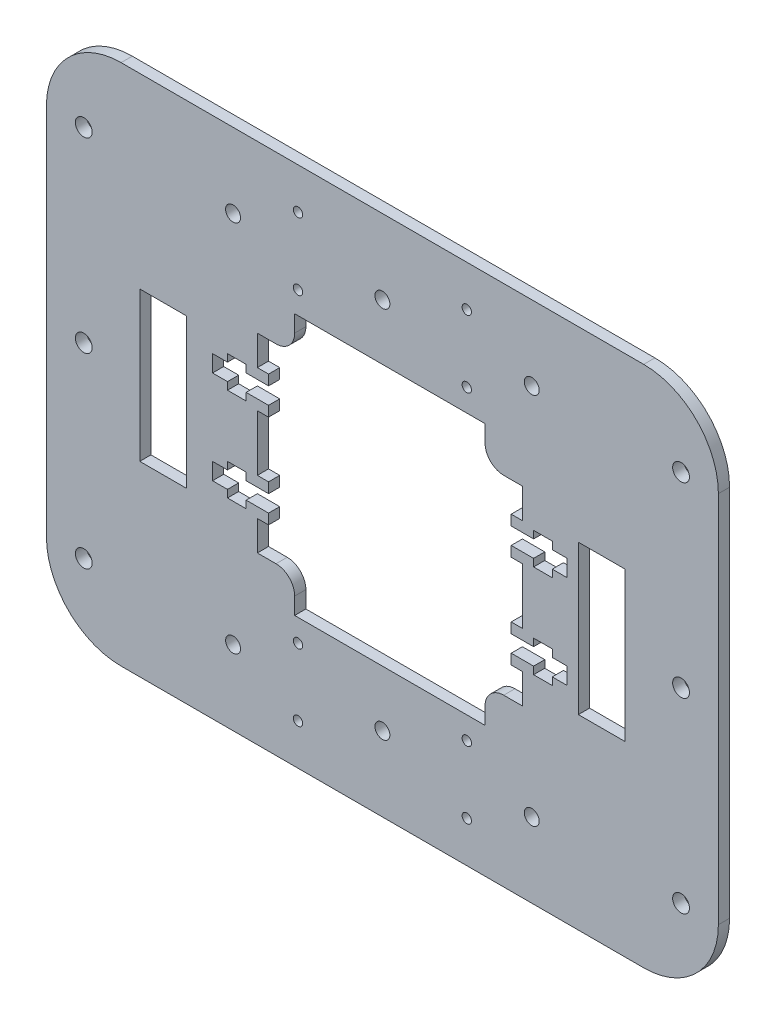
SolidWorks part; units mm, degrees
ref_plane "前视基准面" through (0, 0, 0) normal (0, 0, 1) x (1, 0, 0)
ref_plane "上视基准面" through (0, 0, 0) normal (0, 1, 0) x (1, 0, 0)
ref_plane "右视基准面" through (0, 0, 0) normal (1, 0, 0) x (0, 0, -1)
sketch "草图1" plane through (0, 0, 0) normal (0, 0, 1) x (1, 0, 0)
  line L1 (-90, 70) -> (90, 70)
  line L2 (-90, 70) -> (-90, -70)
  line L3 (-90, -70) -> (90, -70)
  line L4 (90, 70) -> (90, -70)
  line L5 (-90, 70) -> (90, -70) construction
  line L6 (-90, -70) -> (90, 70) construction
  line L11 (-33.5, 35) -> (37.5, 35)
  line L12 (-33.5, 35) -> (-33.5, -35)
  line L13 (-33.5, -35) -> (37.5, -35)
  line L14 (37.5, 35) -> (37.5, -35)
  line L15 (-33.5, 35) -> (37.5, -35) construction
  line L16 (-33.5, -35) -> (37.5, 35) construction
  line L17 (-33.5, 35) -> (-23.5, 35)
  line L18 (-33.5, 35) -> (-33.5, 25.5)
  line L19 (-33.5, 25.5) -> (-23.5, 25.5)
  line L20 (-23.5, 35) -> (-23.5, 25.5)
  line L21 (-33.5, -35) -> (-23.5, -35)
  line L22 (-33.5, -35) -> (-33.5, -25.5)
  line L23 (-33.5, -25.5) -> (-23.5, -25.5)
  line L24 (-23.5, -35) -> (-23.5, -25.5)
  line L25 (37.5, -35) -> (27.5, -35)
  line L26 (37.5, -35) -> (37.5, -25.5)
  line L27 (37.5, -25.5) -> (27.5, -25.5)
  line L28 (27.5, -35) -> (27.5, -25.5)
  line L29 (37.5, 35) -> (27.5, 35)
  line L30 (37.5, 35) -> (37.5, 25.5)
  line L31 (37.5, 25.5) -> (27.5, 25.5)
  line L32 (27.5, 35) -> (27.5, 25.5)
  point P0 (0, 0)
  point P5 (0, 0)
  point P6 (2, 0)
  dimension "D1" = 140
  dimension "D2" = 180
  dimension "D3" = 70
  dimension "D4" = 71
  dimension "D5" = 2
  dimension "D6" = 9.5
  dimension "D7" = 10
  dimension "D8" = 9.5
  dimension "D9" = 10
  dimension "D10" = 9.5
  dimension "D11" = 10
  dimension "D12" = 9.5
  dimension "D13" = 10
extrude "凸台-拉伸1" add sketch "草图1" along normal mid plane 3 contours L4 L1 L2 L3 L11 L14 L13 L12 | L13 L24 L23 L12 | L28 L13 L14 L27 | L11 L32 L31 L14 | L20 L11 L12 L19
fillet "圆角1" radius 20 4 edges at (-90, -70, 0) (-90, 70, 0) (90, 70, 0) (90, -70, 0)
fillet "圆角2" radius 5 4 edges at (-23.5, 25.5, 0) (27.5, 25.5, 0) (27.5, -25.5, 0) (-23.5, -25.5, 0)
sketch "草图2" plane through (0, 0, 1.5) normal (0, 0, 1) x (1, 0, 0)
  line L0 (90, 50) -> (90, -50) construction
  line L1 (52.5, 20) -> (65, 20)
  line L2 (52.5, 20) -> (52.5, -20)
  line L3 (52.5, -20) -> (65, -20)
  line L4 (65, 20) -> (65, -20)
  line L5 (52.5, 20) -> (65, -20) construction
  line L6 (52.5, -20) -> (65, 20) construction
  line L7 (37.5, 25.5) -> (37.5, -25.5) construction
  point P0 (58.75, 0)
  dimension "D1" = 25
  dimension "D2" = 15
  dimension "D3" = 40
  dimension "D4" = 20
extrude "切除-拉伸1" cut sketch "草图2" against normal blind 3
sketch "草图3" plane through (0, 0, 1.5) normal (0, 0, 1) x (1, 0, 0)
  line L5 (2, 35) -> (2, -35) construction
  line L10 (-23.5, 35) -> (27.5, 35) construction
  line L11 (-23.5, -35) -> (27.5, -35) construction
  line L12 (-33.5, 25.5) -> (-33.5, -25.5) construction
  line L13 (-33.5, 17.5) -> (-30.5, 17.5)
  line L14 (-33.5, 17.5) -> (-33.5, 7.5)
  line L15 (-33.5, 7.5) -> (-30.5, 7.5)
  line L16 (-30.5, 17.5) -> (-30.5, 7.5)
  line L17 (37.5, -17.5) -> (34.5, -17.5)
  line L18 (-33.5, -7.5) -> (-30.5, -7.5)
  line L19 (-33.5, -7.5) -> (-33.5, -17.5)
  line L20 (-33.5, -17.5) -> (-30.5, -17.5)
  line L21 (-30.5, -7.5) -> (-30.5, -17.5)
  line L22 (34.5, -7.5) -> (34.5, -17.5)
  line L23 (37.5, -7.5) -> (34.5, -7.5)
  line L24 (37.5, -7.5) -> (37.5, -17.5)
  line L25 (37.5, 7.5) -> (34.5, 7.5)
  line L26 (34.5, 17.5) -> (34.5, 7.5)
  line L27 (37.5, 17.5) -> (34.5, 17.5)
  line L28 (37.5, 17.5) -> (37.5, 7.5)
  dimension "D1" = 10
  dimension "D2" = 3
  dimension "D3" = 10
  dimension "D4" = 3
  dimension "D5" = 15
  dimension "D6" = 7.5
extrude "凸台-拉伸2" add sketch "草图3" against normal blind 3
sketch "草图5" plane through (0, 0, 1.5) normal (0, 0, 1) x (1, 0, 0)
  line L0 (-30.5, 14.75) -> (-36.5, 14.75)
  line L1 (-30.5, 7.5) -> (-30.5, 17.5) construction
  line L2 (-36.5, 14.75) -> (-36.5, 16.75)
  line L3 (-36.5, 16.75) -> (-41.5, 16.75)
  line L4 (-41.5, 16.75) -> (-41.5, 14.75)
  line L5 (-41.5, 14.75) -> (-45.5, 14.75)
  line L6 (-45.5, 14.75) -> (-45.5, 10.25)
  line L7 (-45.5, 10.25) -> (-41.5, 10.25)
  line L8 (-41.5, 10.25) -> (-41.5, 8.25)
  line L9 (-41.5, 8.25) -> (-36.5, 8.25)
  line L10 (-36.5, 8.25) -> (-36.5, 10.25)
  line L11 (-36.5, 10.25) -> (-30.5, 10.25)
  line L12 (-33.5, 7.5) -> (-30.5, 7.5) construction
  line L13 (-30.5, 10.25) -> (-30.5, 14.75)
  line L14 (55, 0) -> (-55, 0) construction
  line L15 (-36.5, -10.25) -> (-30.5, -10.25)
  line L16 (-36.5, -8.25) -> (-36.5, -10.25)
  line L17 (-41.5, -8.25) -> (-36.5, -8.25)
  line L18 (-41.5, -10.25) -> (-41.5, -8.25)
  line L19 (-45.5, -10.25) -> (-41.5, -10.25)
  line L20 (-45.5, -14.75) -> (-45.5, -10.25)
  line L21 (-41.5, -14.75) -> (-45.5, -14.75)
  line L22 (-41.5, -16.75) -> (-41.5, -14.75)
  line L23 (-36.5, -16.75) -> (-41.5, -16.75)
  line L24 (-36.5, -14.75) -> (-36.5, -16.75)
  line L25 (-30.5, -14.75) -> (-36.5, -14.75)
  line L26 (-30.5, -10.25) -> (-30.5, -14.75)
  line L27 (2, 35) -> (2, -35) construction
  line L28 (-23.5, 35) -> (27.5, 35) construction
  line L29 (-23.5, -35) -> (27.5, -35) construction
  line L30 (40.5, -8.25) -> (40.5, -10.25)
  line L31 (45.5, -8.25) -> (40.5, -8.25)
  line L32 (45.5, -10.25) -> (45.5, -8.25)
  line L33 (49.5, -10.25) -> (45.5, -10.25)
  line L34 (49.5, -14.75) -> (49.5, -10.25)
  line L35 (45.5, -14.75) -> (49.5, -14.75)
  line L36 (45.5, -16.75) -> (45.5, -14.75)
  line L37 (40.5, -16.75) -> (45.5, -16.75)
  line L38 (40.5, -14.75) -> (40.5, -16.75)
  line L39 (34.5, -14.75) -> (40.5, -14.75)
  line L40 (34.5, -10.25) -> (34.5, -14.75)
  line L41 (40.5, -10.25) -> (34.5, -10.25)
  line L42 (40.5, 10.25) -> (34.5, 10.25)
  line L43 (40.5, 8.25) -> (40.5, 10.25)
  line L44 (45.5, 8.25) -> (40.5, 8.25)
  line L45 (45.5, 10.25) -> (45.5, 8.25)
  line L46 (49.5, 10.25) -> (45.5, 10.25)
  line L47 (49.5, 14.75) -> (49.5, 10.25)
  line L48 (45.5, 14.75) -> (49.5, 14.75)
  line L49 (45.5, 16.75) -> (45.5, 14.75)
  line L50 (40.5, 16.75) -> (45.5, 16.75)
  line L51 (40.5, 14.75) -> (40.5, 16.75)
  line L52 (34.5, 14.75) -> (40.5, 14.75)
  line L53 (34.5, 10.25) -> (34.5, 14.75)
  dimension "D1" = 6
  dimension "D2" = 2
  dimension "D3" = 5
  dimension "D4" = 2
  dimension "D5" = 4
  dimension "D6" = 4.5
  dimension "D7" = 4
  dimension "D8" = 2
  dimension "D9" = 5
  dimension "D10" = 2
  dimension "D11" = 4.5
  dimension "D12" = 2.75
extrude "切除-拉伸2" cut sketch "草图5" against normal blind 3
sketch "草图6" plane through (0, 0, 1.5) normal (0, 0, 1) x (1, 0, 0)
  line L0 (55, 0) -> (-55, 0) construction
  line L1 (-80, 50) -> (80, 50) construction
  line L2 (-80, 50) -> (-80, -50) construction
  line L3 (-80, -50) -> (80, -50) construction
  line L4 (80, 50) -> (80, -50) construction
  line L5 (-80, 50) -> (80, -50) construction
  line L6 (-80, -50) -> (80, 50) construction
  line L7 (-22.605, -41) -> (22.605, -41) construction
  line L8 (-22.605, -41) -> (-22.605, -59) construction
  line L9 (-22.605, -59) -> (22.605, -59) construction
  line L10 (22.605, -41) -> (22.605, -59) construction
  line L11 (-22.605, -41) -> (22.605, -59) construction
  line L12 (-22.605, -59) -> (22.605, -41) construction
  circle A0 centre (-80, 50) radius 2.25
  circle A1 centre (80, 50) radius 2.25
  circle A2 centre (80, -50) radius 2.25
  circle A3 centre (-80, -50) radius 2.25
  circle A4 centre (-22.605, -41) radius 1.25
  circle A5 centre (22.605, -41) radius 1.25
  circle A6 centre (22.605, -59) radius 1.25
  circle A7 centre (-22.605, -59) radius 1.25
  circle A8 centre (22.605, 59) radius 1.25
  circle A9 centre (22.605, 41) radius 1.25
  circle A10 centre (-22.605, 41) radius 1.25
  circle A11 centre (-22.605, 59) radius 1.25
  circle A12 centre (0, 50) radius 2
  circle A13 centre (40, 50) radius 2
  circle A14 centre (-40, 50) radius 2
  circle A15 centre (0, -50) radius 2
  circle A16 centre (40, -50) radius 2
  circle A17 centre (-40, -50) radius 2
  circle A18 centre (-80, 0) radius 2.25
  circle A19 centre (80, 0) radius 2.25
  point P0 (0, 0)
  point P10 (0, -50)
  dimension "D3" = 4.5
  dimension "D4" = 4.5
  dimension "D5" = 4.5
  dimension "D6" = 4.5
  dimension "D9" = 2.5
  dimension "D10" = 2.5
  dimension "D11" = 2.5
  dimension "D12" = 2.5
  dimension "D13" = 4
  dimension "D14" = 4
  dimension "D15" = 4
  dimension "D16" = 40
  dimension "D17" = 40
  dimension "D18" = 4.5
  dimension "D19" = 4.5
  dimension "D1" = 100
  dimension "D2" = 160
  dimension "D7" = 18
  dimension "D8" = 45.21
extrude "切除-拉伸3" cut sketch "草图6" against normal blind 10
mirror "镜向1" about plane through (0, 0, 0) normal (1, 0, 0) of "切除-拉伸1"
